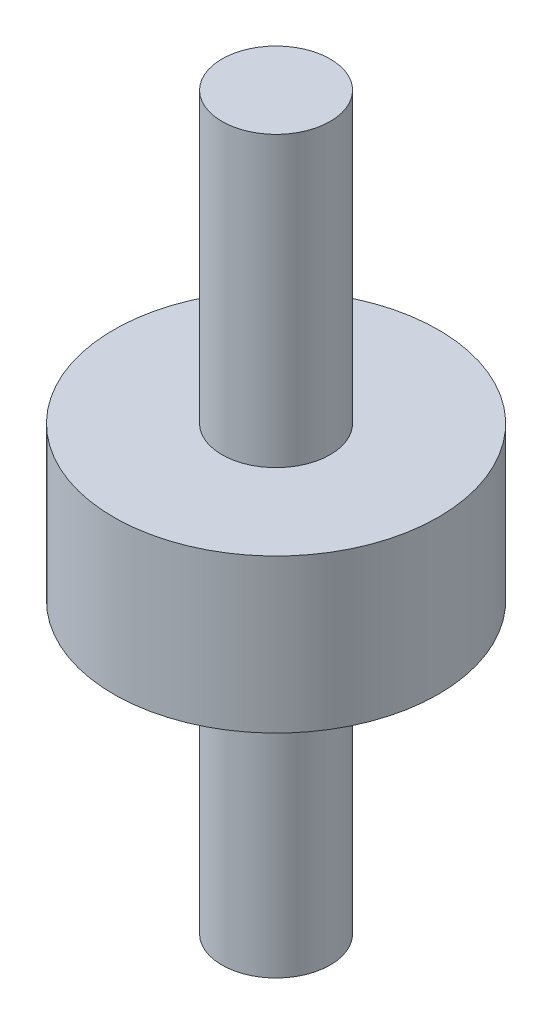
SolidWorks part; units mm, degrees
ref_plane "Front Plane" through (0, 0, 0) normal (0, 0, 1) x (1, 0, 0)
ref_plane "Top Plane" through (0, 0, 0) normal (0, 1, 0) x (1, 0, 0)
ref_plane "Right Plane" through (0, 0, 0) normal (1, 0, 0) x (0, 0, -1)
sketch "Sketch1" plane through (0, 0, 0) normal (0, 0, 1) x (1, 0, 0)
  line L0 (0, 40.5) -> (-3, 40.5)
  line L1 (-3, 40.5) -> (-3, 24.5)
  line L2 (-3, 24.5) -> (-9, 24.5)
  line L3 (-9, 24.5) -> (-9, 16)
  line L4 (-9, 16) -> (-3, 16)
  line L5 (-3, 16) -> (-3, 0)
  line L6 (-3, 0) -> (0, 0)
  line L7 (0, 0) -> (0, 40.5)
  dimension "D1" = 3
  dimension "D2" = 16
  dimension "D3" = 16
  dimension "D4" = 8.5
  dimension "D5" = 9
revolve "Revolve1" add sketch "Sketch1" angle 360 about L7
